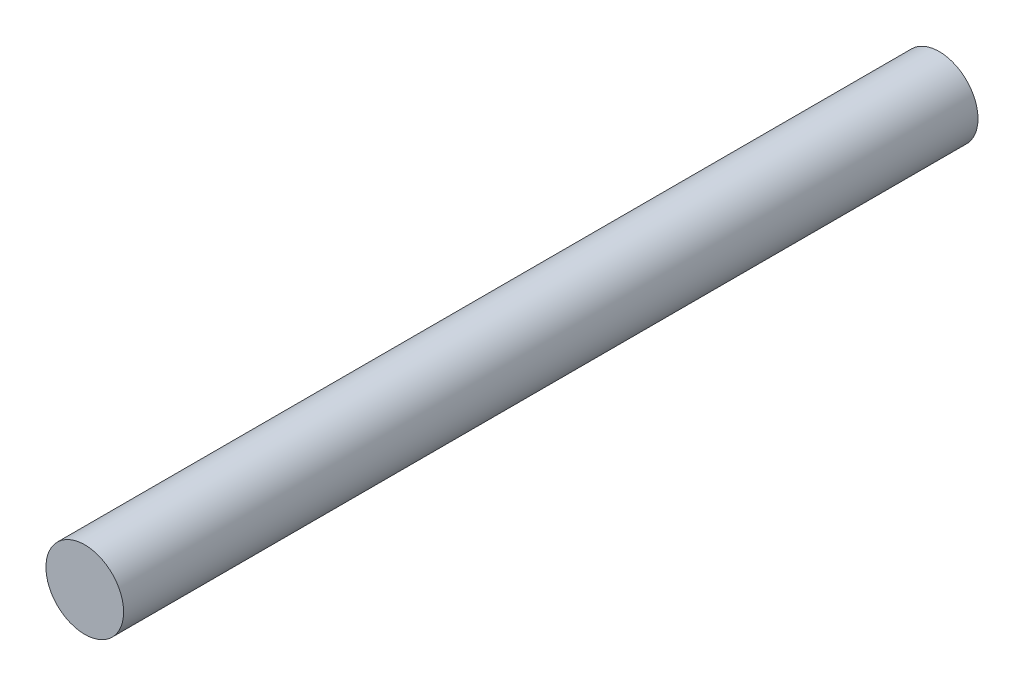
SolidWorks part; units mm, degrees
ref_plane "Front Plane" through (0, 0, 0) normal (0, 0, 1) x (1, 0, 0)
ref_plane "Top Plane" through (0, 0, 0) normal (0, 1, 0) x (1, 0, 0)
ref_plane "Right Plane" through (0, 0, 0) normal (1, 0, 0) x (0, 0, -1)
sketch "Sketch1" plane through (0, 0, 0) normal (0, 0, 1) x (1, 0, 0)
  circle A0 centre (0, 0) radius 12
  dimension "D1" = 24
extrude "Boss-Extrude1" add sketch "Sketch1" along normal mid plane 264
